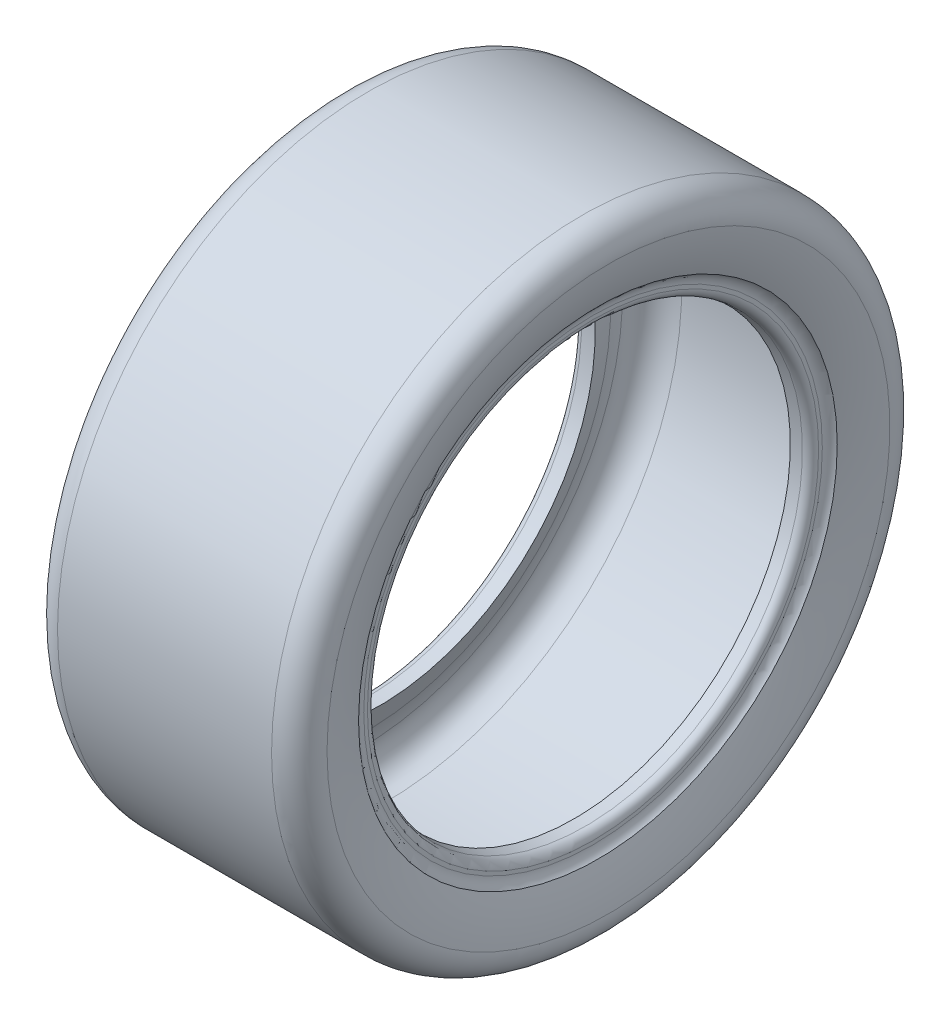
SolidWorks part; units mm, degrees
ref_plane "Front Plane" through (0, 0, 0) normal (0, 0, 1) x (1, 0, 0)
ref_plane "Top Plane" through (0, 0, 0) normal (0, 1, 0) x (1, 0, 0)
ref_plane "Right Plane" through (0, 0, 0) normal (1, 0, 0) x (0, 0, -1)
ref_plane "Plane1" through (0, 0, 0) normal (0, 0, -1) x (-1, 0, 0)
sketch "Sketch1" plane through (0, 0, 0) normal (0, 0, -1) x (-1, 0, 0)
  line L0 (-99.342, 225) -> (38.4905, 225)
  line L1 (52.3491, 185.0599) -> (42.2756, 163.3405)
  line L2 (50.7452, 235) -> (-111.1745, 235)
  line L3 (-113.5578, 164.3139) -> (-105.1431, 163.5777)
  line L4 (-105.1431, 163.5777) -> (-113.82, 184.8583)
  line L5 (-131.1745, 0) -> (70.7452, 0) construction
  arc A0 (38.4905, 225) -> (57.7246, 199.5182) centre (38.4905, 205) cw
  arc A1 (57.7246, 199.5182) -> (52.3491, 185.0599) centre (-37.0837, 226.5391) cw
  arc A2 (53.5578, 164.3139) -> (59.4, 170.6895) centre (53, 170.6895) ccw
  arc A3 (61.421, 180.8527) -> (70.5748, 212.3948) centre (-37.0837, 226.5391) ccw
  arc A4 (70.5748, 212.3948) -> (50.7452, 235) centre (50.7452, 215) ccw
  arc A5 (-111.1745, 235) -> (-131.0655, 212.9152) centre (-111.1745, 215) ccw
  arc A6 (-131.0655, 212.9152) -> (-123.0799, 181.0827) centre (-15.2345, 225.0553) ccw
  arc A7 (-123.0799, 181.0827) -> (-119.4, 173.4769) centre (-129.1, 173.4769) cw
  arc A8 (-119.4, 170.6895) -> (-113.5578, 164.3139) centre (-113, 170.6895) ccw
  arc A9 (-113.82, 184.8583) -> (-118.7965, 200.3611) centre (-15.2345, 225.0553) cw
  arc A10 (-118.7965, 200.3611) -> (-99.342, 225) centre (-99.342, 205) cw
  spline S0 degree 3 poles (42.2756, 163.3405) (46.0382, 163.6424) (49.7975, 163.9849) (53.5578, 164.3139) knots 0 0 0 0 1 1 1 1
  spline S1 degree 3 poles (59.4, 170.6895) (59.4, 172.1017) (59.4, 173.5139) (59.4, 174.9261) knots 0 0 0 0 1 1 1 1
  spline S2 degree 3 poles (59.4, 174.9261) (59.405, 175.107) (59.4099, 175.2844) (59.4146, 175.4582) knots 0 0 0 0 1 1 1 1
  spline S3 degree 3 poles (59.4146, 175.4582) (59.4821, 175.961) (59.5495, 176.4637) (59.617, 176.9664) knots 0 0 0 0 1 1 1 1
  spline S4 degree 3 poles (59.617, 176.9664) (59.9167, 177.7345) (60.5415, 179.7558) (61.421, 180.8527) knots 0 0 0 0 1 1 1 1
  spline S5 degree 3 poles (-119.4, 173.4769) (-119.4, 172.5478) (-119.4, 171.6187) (-119.4, 170.6895) knots 0 0 0 0 1 1 1 1
revolve "Revolve1" add sketch "Sketch1" angle 360 about L5
ref_plane "Plane2" through (0, 0, 235) normal (0, 0, 1) x (1, 0, 0)
sketch "Sketch2" plane through (0, 0, 235) normal (0, 0, 1) x (1, 0, 0)
  line L4 (111.1745, -79.179) -> (-50.7452, -79.179) construction
  line L5 (30.2146, -79.179) -> (30.2146, -524.5703) construction
ref_plane "Plane4" through (30.2146, 0, 0) normal (-1, 0, 0) x (0, -1, 0)
